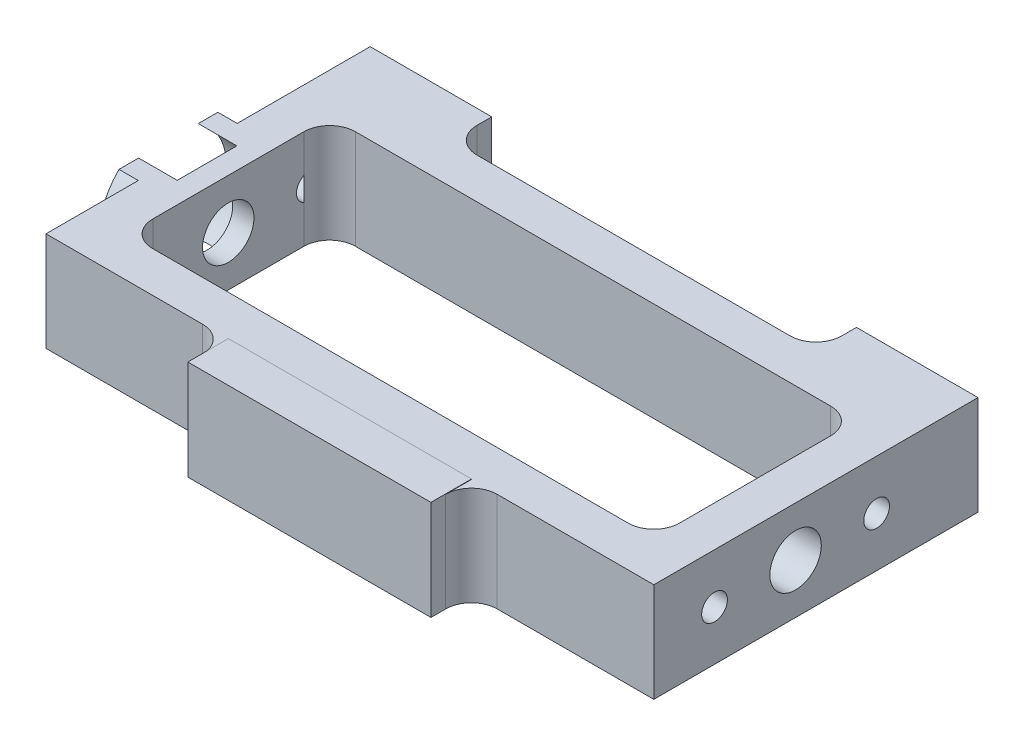
SolidWorks part; units mm, degrees
material "AISI 4340 Acero recocido"
ref_plane "Alzado" through (0, 0, 0) normal (0, 0, 1) x (1, 0, 0)
ref_plane "Planta" through (0, 0, 0) normal (0, 1, 0) x (1, 0, 0)
ref_plane "Vista lateral" through (0, 0, 0) normal (1, 0, 0) x (0, 0, -1)
other "Centro de masa"
sketch "Croquis1" plane through (0, 0, 0) normal (0, 1, 0) x (1, 0, 0)
  line L1 (75, -45) -> (-75, -45)
  line L2 (75, -45) -> (75, 45)
  line L3 (75, 45) -> (-75, 45)
  line L4 (-75, -45) -> (-75, 45)
  line L5 (75, -45) -> (-75, 45) construction
  line L6 (75, 45) -> (-75, -45) construction
  point P0 (0, 0)
  dimension "D1" = 150
  dimension "D2" = 90
extrude "Saliente-Extruir1" add sketch "Croquis1" along normal blind 24.5
sketch "Croquis3" plane through (0, 24.5, 0) normal (0, 1, 0) x (1, 0, 0)
  line L0 (75, 45) -> (-75, 45) construction
  line L1 (58.65, -25) -> (-58.65, -25)
  line L2 (65, -18.65) -> (65, 18.65)
  line L3 (58.65, 25) -> (-58.65, 25)
  line L4 (-65, -18.65) -> (-65, 18.65)
  line L5 (65, -25) -> (-65, 25) construction
  line L6 (65, 25) -> (-65, -25) construction
  line L7 (75, -45) -> (75, 45) construction
  line L8 (0, 0) -> (0, 35) construction
  line L9 (-75, -45) -> (-30, -45)
  line L10 (-75, -45) -> (-75, -35)
  line L11 (-75, -35) -> (-36.35, -35)
  line L12 (-30, -45) -> (-30, -41.35)
  line L13 (75, -45) -> (30, -45)
  line L14 (75, -45) -> (75, -35)
  line L15 (75, -35) -> (36.35, -35)
  line L16 (30, -45) -> (30, -41.35)
  line L17 (-45, 45) -> (45, 45)
  line L18 (-45, 45) -> (-45, 41.35)
  line L19 (-38.65, 35) -> (38.65, 35)
  line L20 (45, 45) -> (45, 41.35)
  line L21 (-75, -45) -> (-75, -25) construction
  line L22 (-75, 45) -> (-75, -45) construction
  line L23 (-58.65, -25) -> (-75, -25) construction
  line L24 (-75, -45) -> (75, -45) construction
  arc A0 (65, 18.65) -> (58.65, 25) centre (58.65, 18.65) ccw
  arc A1 (58.65, -25) -> (65, -18.65) centre (58.65, -18.65) ccw
  arc A2 (-58.65, -25) -> (-65, -18.65) centre (-58.65, -18.65) cw
  arc A3 (-58.65, 25) -> (-65, 18.65) centre (-58.65, 18.65) ccw
  arc A4 (36.35, -35) -> (30, -41.35) centre (36.35, -41.35) ccw
  arc A5 (-36.35, -35) -> (-30, -41.35) centre (-36.35, -41.35) cw
  arc A6 (38.65, 35) -> (45, 41.35) centre (38.65, 41.35) ccw
  arc A7 (-45, 41.35) -> (-38.65, 35) centre (-38.65, 41.35) ccw
  point P0 (0, 0)
  point P42 (30, -35)
  dimension "D1" = 6.35
  dimension "D4" = 6.35
  dimension "D2" = 20
  dimension "D3" = 10
  dimension "D5" = 90
  dimension "D6" = 60
extrude "Cortar-Extruir2" cut sketch "Croquis3" against normal through all
sketch "Croquis2" plane through (75, 0, 0) normal (1, 0, 0) x (0, 0, -1)
  line L0 (-45, 12.25) -> (45, 12.25) construction
  line L1 (45, 24.5) -> (45, 0) construction
  line L2 (-45, 24.5) -> (-45, 0) construction
  circle A0 centre (-0.0193, 12.2559) radius 6.35
  circle A1 centre (-20.0193, 12.25) radius 3.175
  circle A2 centre (19.9807, 12.25) radius 3.175
  dimension "D3" = 12.7
  dimension "D4" = 6.35
  dimension "D1" = 40
  dimension "D2" = 20
sketch "Croquis6" plane through (-75, 0, 0) normal (-1, 0, 0) x (0, 0, 1)
  circle A0 centre (0.0193, 12.2559) radius 14.2875
  dimension "D1" = 28.575
extrude "Cortar-Extruir3" cut sketch "Croquis6" against normal blind 4.7625
extrude "Cortar-Extruir4" cut sketch "Croquis2" against normal up to surface (5.2375 mm away) from surface at -140 contours A0
extrude "Cortar-Extruir1" cut sketch "Croquis2" against normal blind 41 contours A0
sketch "Croquis7" plane through (-75, 0, 0) normal (-1, 0, 0) x (0, 0, 1)
  line L0 (-12.1848, 24.5) -> (-7.3438, 24.5)
  line L1 (-45, 24.5) -> (-7.3438, 24.5) construction
  line L2 (7.3825, 24.5) -> (12.2235, 24.5)
  line L3 (12.2115, 0) -> (7.3627, 0)
  line L4 (7.3627, 0) -> (35, 0) construction
  line L5 (-7.324, 0) -> (-12.1728, 0)
  arc A0 (-7.3438, 24.5) -> (-7.324, 0) centre (0.0193, 12.2559) ccw
  arc A1 (-12.1848, 24.5) -> (-12.1728, 0) centre (0.0193, 12.2559) ccw
  arc A2 (12.2115, 0) -> (12.2235, 24.5) centre (0.0193, 12.2559) ccw
  arc A3 (7.3825, 24.5) -> (7.3627, 0) centre (0.0193, 12.2559) cw
  dimension "D1" = 3
extrude "Saliente-Extruir2" add sketch "Croquis7" along normal blind 4.7625
sketch "Croquis8" plane through (0, 24.5, 0) normal (0, 1, 0) x (1, 0, 0)
  line L0 (75, -35) -> (36.35, -35) construction
  line L1 (-30, -45) -> (30, -45)
  line L2 (-30, -45) -> (-30, -35)
  line L3 (-30, -35) -> (30, -35)
  line L4 (30, -45) -> (30, -35)
sketch "Croquis9" [suppressed] plane through (0, 24.5, 0) normal (0, 1, 0) x (1, 0, 0)
  line L1 (100, -50.8) -> (-100, -50.8)
  line L2 (100, -50.8) -> (100, 50.8)
  line L3 (100, 50.8) -> (-100, 50.8)
  line L4 (-100, -50.8) -> (-100, 50.8)
  line L5 (100, -50.8) -> (-100, 50.8) construction
  line L6 (100, 50.8) -> (-100, -50.8) construction
  point P0 (0, 0)
  dimension "D1" = 200
  dimension "D2" = 101.6
extrude "Saliente-Extruir3" add sketch "Croquis8" along normal blind 0.1
equation "\"anchofilo\"= 1"
